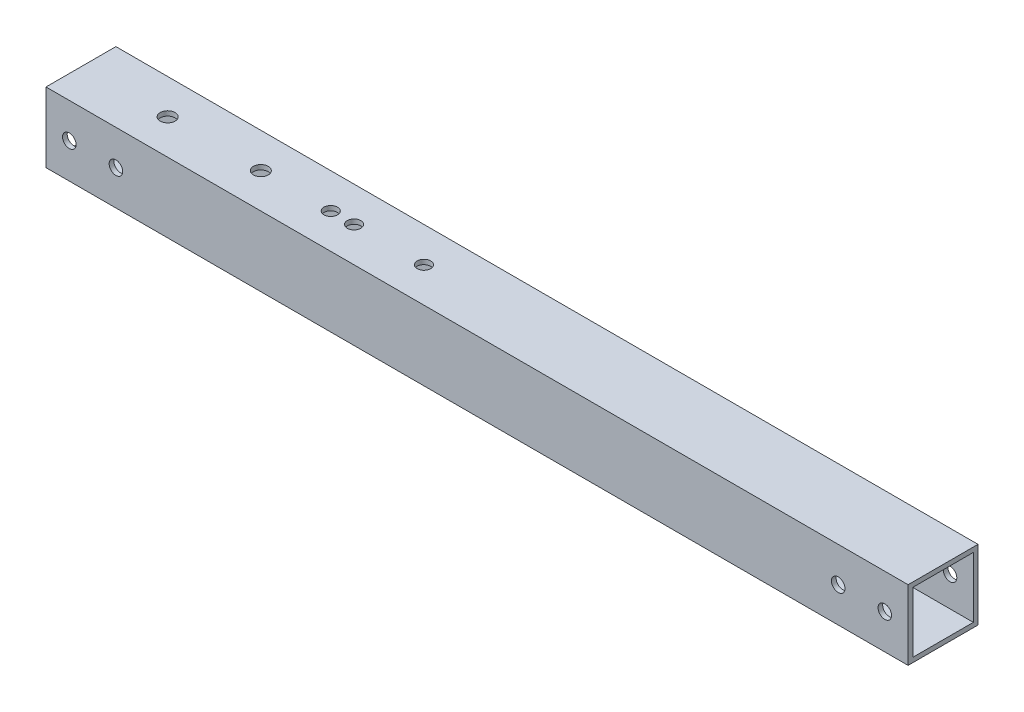
SolidWorks part; units mm, degrees
material "Thornel Mat VMA"
ref_plane "前视基准面" through (0, 0, 0) normal (0, 0, 1) x (1, 0, 0)
ref_plane "上视基准面" through (0, 0, 0) normal (0, 1, 0) x (1, 0, 0)
ref_plane "右视基准面" through (0, 0, 0) normal (1, 0, 0) x (0, 0, -1)
other "Configuration Table"
sketch "草图1" plane through (0, 0, 0) normal (1, 0, 0) x (0, 0, -1)
  line L0 (-6.5, -6.5) -> (-6.5, 6.5)
  line L1 (-7.5, -7.5) -> (7.5, -7.5)
  line L2 (-7.5, -7.5) -> (-7.5, 7.5)
  line L3 (-7.5, 7.5) -> (7.5, 7.5)
  line L4 (7.5, -7.5) -> (7.5, 7.5)
  line L5 (-7.5, -7.5) -> (7.5, 7.5) construction
  line L6 (-7.5, 7.5) -> (7.5, -7.5) construction
  line L7 (-6.5, 6.5) -> (6.5, 6.5)
  line L8 (6.5, -6.5) -> (6.5, 6.5)
  line L9 (-6.5, -6.5) -> (6.5, -6.5)
  point P0 (0, 0)
  dimension "D1" = 15
  dimension "D2" = 15
  dimension "D3" = 1
extrude "凸台-拉伸1" add sketch "草图1" along normal blind 185
sketch "草图2" plane through (0, 0, 7.5) normal (0, 0, 1) x (1, 0, 0)
  line L0 (0, 0) -> (48.7227, 0) construction
  circle A0 centre (180, 0) radius 1.45 construction
  circle A1 centre (170, 0) radius 1.45 construction
  circle A2 centre (180, 0) radius 1.45
  circle A3 centre (170, 0) radius 1.45
  circle A4 centre (5, 0) radius 1.45
  circle A5 centre (15, 0) radius 1.45
  dimension "D1" = 5
  dimension "D2" = 10
  dimension "D3" = 2.9
extrude "切除-拉伸1" cut sketch "草图2" against normal through all
sketch "草图3" plane through (0, 7.5, 0) normal (0, 1, 0) x (1, 0, 0)
  line L0 (-7.8761, 0) -> (193.4878, 0) construction
  circle A0 centre (38.6, 0) radius 1.6 construction
  circle A1 centre (18.6, 0) radius 1.6 construction
  circle A2 centre (38.6, 0) radius 1.6
  circle A3 centre (18.6, 0) radius 1.6
  circle A4 centre (53.6, 0) radius 1.45
  circle A5 centre (58.6, 0) radius 1.45
  circle A6 centre (73.6, 0) radius 1.45
  dimension "D1" = 15
  dimension "D2" = 20
  dimension "D3" = 20
  dimension "D4" = 2.9
extrude "切除-拉伸2" cut sketch "草图3" against normal through all
